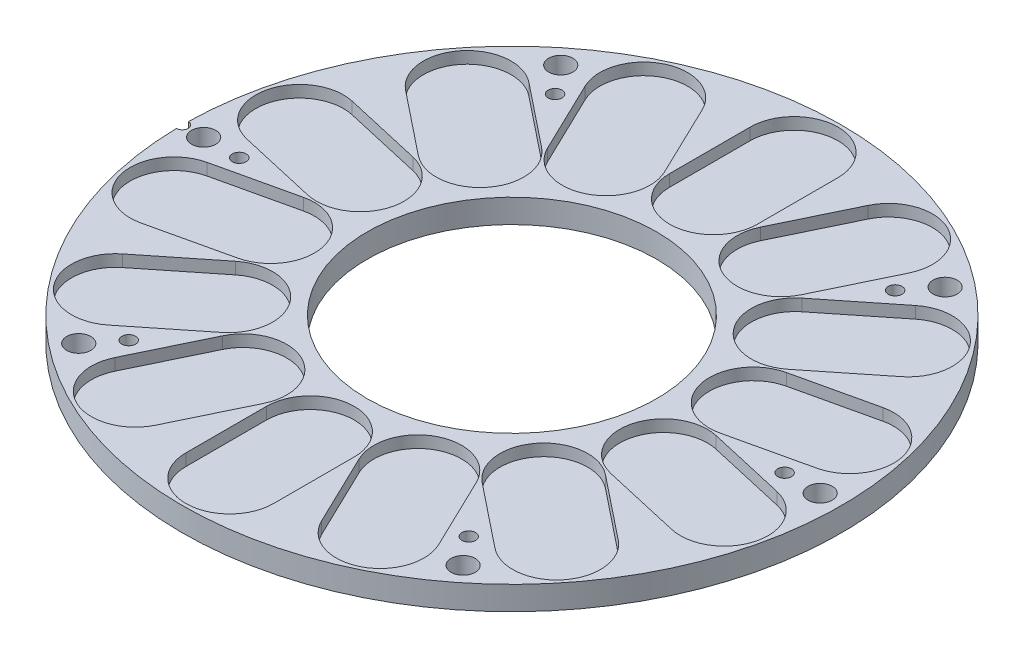
SolidWorks part; units mm, degrees
material "GFRP"
ref_plane "正面" through (0, 0, 0) normal (0, 0, 1) x (1, 0, 0)
ref_plane "平面" through (0, 0, 0) normal (0, 1, 0) x (1, 0, 0)
ref_plane "右側面" through (0, 0, 0) normal (1, 0, 0) x (0, 0, -1)
sketch "ｽｹｯﾁ1" plane through (0, 0, 0) normal (0, 1, 0) x (1, 0, 0)
  circle A0 centre (0, 0) radius 139
  circle A1 centre (0, 0) radius 61
  dimension "D1" = 278
  dimension "D2" = 122
extrude "ﾎﾞｽ - 押し出し1" add sketch "ｽｹｯﾁ1" along normal blind 10
sketch "ｽｹｯﾁ2" plane through (0, 10, 0) normal (0, 1, 0) x (1, 0, 0)
  line L0 (0, 119) -> (0, 85) construction
  line L1 (18.5, 119) -> (18.5, 85)
  line L2 (-18.5, 119) -> (-18.5, 85)
  arc A0 (18.5, 119) -> (-18.5, 119) centre (0, 119) ccw
  arc A1 (-18.5, 85) -> (18.5, 85) centre (0, 85) ccw
  point P2 (0, 102)
  dimension "D2" = 34
  dimension "D3" = 102
  dimension "D1" = 37
extrude "ｶｯﾄ - 押し出し1" cut sketch "ｽｹｯﾁ2" against normal blind 5
pattern_circular "円形ﾊﾟﾀｰﾝ2" count 14 over 360 about axis through (0, 0, 0) along (0, 1, 0) of "ｶｯﾄ - 押し出し1"
sketch "ｽｹｯﾁ3" plane through (0, 10, 0) normal (0, 1, 0) x (1, 0, 0)
  line L0 (0, 0) -> (130, 0) construction
  circle A0 centre (130, 0) radius 5.1
  dimension "D1" = 10.2
  dimension "D2" = 130
extrude "ｶｯﾄ - 押し出し2" cut sketch "ｽｹｯﾁ3" against normal through all
sketch "ｽｹｯﾁ8" plane through (0, 10, 0) normal (0, 1, 0) x (1, 0, 0)
  circle A0 centre (81.0537, 101.6381) radius 5.1
  point P5 (130, 0)
  dimension "D1" = 10.2
  dimension "D2" = 130
  dimension "D3" = 51.429
extrude "ｶｯﾄ - 押し出し3" cut sketch "ｽｹｯﾁ8" against normal through all
sketch "ｽｹｯﾁ10" plane through (0, 10, 0) normal (0, 1, 0) x (1, 0, 0)
  line L0 (-139, 0) -> (0, 0) construction
  circle A1 centre (0, 0) radius 139 construction
  circle A2 centre (-139, 0) radius 2.5
  dimension "D2" = 5
extrude "ｶｯﾄ - 押し出し4" cut sketch "ｽｹｯﾁ10" against normal through all
mirror "ﾐﾗｰ1" about plane through (0, 0, 0) normal (0, 0, 1) of "ｶｯﾄ - 押し出し3"
mirror "ﾐﾗｰ2" about plane through (0, 0, 0) normal (1, 0, 0) of "ｶｯﾄ - 押し出し2", "ﾐﾗｰ1", "ｶｯﾄ - 押し出し3"
sketch "ｽｹｯﾁ11" plane through (0, 10, 0) normal (0, 1, 0) x (1, 0, 0)
  line L0 (0, 0) -> (130, 0) construction
  line L1 (0, 0) -> (81.0537, 101.6381) construction
  line L2 (0, 139) -> (0, -139) construction
  circle A0 centre (115, 0) radius 5
  circle A1 centre (71.7013, 89.9106) radius 5
  arc A2 (-138.9775, -2.4999) -> (-138.9775, 2.4999) centre (0, 0) ccw construction
  circle A3 centre (71.7013, -89.9106) radius 5
  circle A4 centre (-71.7013, -89.9106) radius 5
  circle A5 centre (-115, 0) radius 5
  circle A6 centre (-71.7013, 89.9106) radius 5
  dimension "D3" = 10
  dimension "D4" = 10
  dimension "D1" = 115
  dimension "D2" = 115
hole_wizard "M5 Base_Plateへの固定用穴" positions "3Dｽｹｯﾁ1" profile "ｽｹｯﾁ12" hole size "M5" standard "JIS" end condition through all
sketch3d "3Dｽｹｯﾁ1"
  point P0 (71.7013, 10, -89.9106)
  point P3 (115, 10, 0)
  point P6 (71.7013, 10, 89.9106)
  point P9 (-71.7013, 10, 89.9106)
  point P12 (-115, 10, 0)
  point P15 (-71.7013, 10, -89.9106)
sketch "ｽｹｯﾁ12" plane through (71.7013, 10, -89.9106) normal (1, 0, 0) x (0, 0, 1)
  line L0 (0, 0) -> (0, 10)
  line L1 (0, 10) -> (2.9, 10)
  line L2 (2.9, 10) -> (2.9, 0)
  line L5 (2.9, 0) -> (0, 0)
  line L11 (0, -6.35) -> (0, 107.95) construction
  dimension "通し穴の直径" = 5.8
  dimension "通し穴の深さ" = 10
